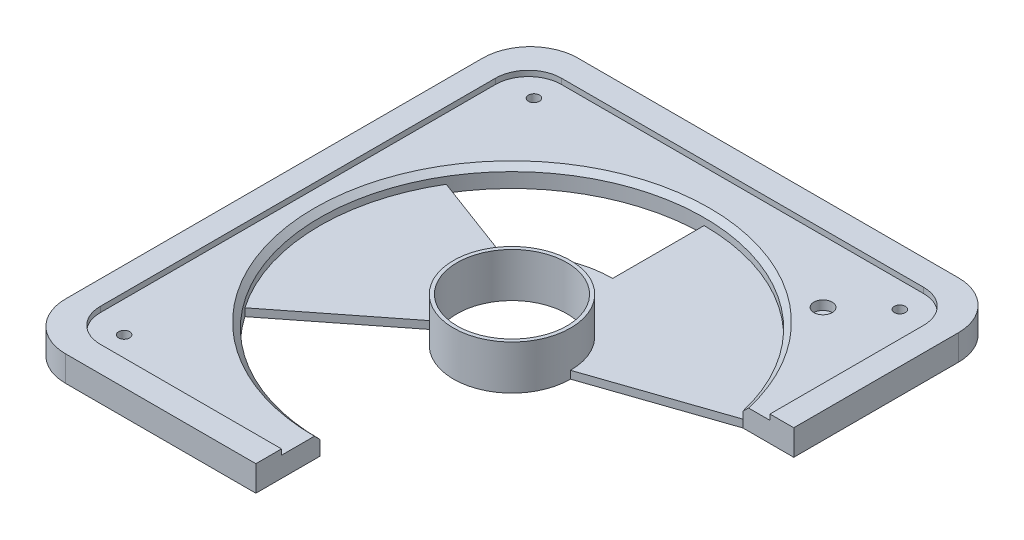
SolidWorks part; units mm, degrees
material "Alumina"
ref_plane "Front Plane" through (0, 0, 0) normal (0, 0, 1) x (1, 0, 0)
ref_plane "Top Plane" through (0, 0, 0) normal (0, 1, 0) x (1, 0, 0)
ref_plane "Right Plane" through (0, 0, 0) normal (1, 0, 0) x (0, 0, -1)
sketch "Sketch1" plane through (0, 0, 0) normal (0, 1, 0) x (1, 0, 0)
  circle A0 centre (0, 0) radius 20.32
  dimension "D1" = 40.64
extrude "Boss-Extrude1" add sketch "Sketch1" along normal blind 15.367
sketch "Sketch2" plane through (0, 15.367, 0) normal (0, 1, 0) x (1, 0, 0)
  circle A0 centre (0, 0) radius 19.05
  dimension "D1" = 38.1
extrude "Cut-Extrude1" cut sketch "Sketch2" against normal through all
sketch "Sketch3" plane through (0, 0, 0) normal (0, 1, 0) x (1, 0, 0)
  line L0 (0, 66.675) -> (0, 34.925)
  line L1 (-26.4041, 22.86) -> (-57.15, 34.3429)
  line L2 (-18.2721, -8.89) -> (-54.9803, -37.719)
  line L3 (20.32, 0) -> (64.9099, 15.24)
  circle A1 centre (0, 0) radius 66.675
  circle A2 centre (0, 0) radius 34.925
  circle A3 centre (0, 0) radius 20.32 construction
  circle A4 centre (0, 0) radius 20.32 construction
  point P8 (-66.675, 0)
  point P9 (20.32, 0)
  dimension "D1" = 133.35
  dimension "D2" = 69.85
  dimension "D3" = 57.15
  dimension "D4" = 22.86
  dimension "D5" = 37.719
  dimension "D6" = 8.89
  dimension "D7" = 15.24
extrude "Boss-Extrude2" add sketch "Sketch3" along normal blind 2.667
sketch "Sketch4" plane through (0, 2.667, 0) normal (0, 1, 0) x (1, 0, 0)
  line L0 (-29.9108, -18.0305) -> (-18.2721, -8.89)
  line L1 (-29.9108, -18.0305) -> (-54.9803, -37.719) construction
  line L2 (34.5831, 4.8749) -> (20.32, 0)
  line L3 (34.5831, 4.8749) -> (64.9099, 15.24) construction
  circle A0 centre (0, 0) radius 20.32 construction
  circle A1 centre (0, 0) radius 20.32 construction
  arc A2 (-29.9108, -18.0305) -> (34.5831, 4.8749) centre (3.5501, -9.996) ccw
  arc A3 (-18.2721, -8.89) -> (20.32, 0) centre (0, 0) ccw
  dimension "D1" = 34.412
  dimension "D2" = 20.32
extrude "Cut-Extrude2" cut sketch "Sketch4" against normal through all
sketch "Sketch6" plane through (0, 2.667, 0) normal (0, 1, 0) x (1, 0, 0)
  circle A0 centre (0, 0) radius 19.05
  dimension "D1" = 38.1
extrude "Cut-Extrude3" cut sketch "Sketch6" against normal through all
sketch "Sketch7" plane through (0, 0, 0) normal (0, 1, 0) x (1, 0, 0)
  line L1 (-82.55, -88.9) -> (82.55, -88.9)
  line L2 (-82.55, -88.9) -> (-82.55, 88.9)
  line L3 (-82.55, 88.9) -> (82.55, 88.9)
  line L4 (82.55, -88.9) -> (82.55, 88.9)
  line L5 (-82.55, -88.9) -> (82.55, 88.9) construction
  line L6 (-82.55, 88.9) -> (82.55, -88.9) construction
  circle A0 centre (0, 0) radius 66.675
  point P0 (0, 0)
  dimension "D3" = 133.35
  dimension "D1" = 165.1
  dimension "D2" = 177.8
extrude "Boss-Extrude3" add sketch "Sketch7" along normal blind 6.985 contours L2 L1 L4 L3 | A0
sketch "Sketch10" plane through (0, 6.985, 0) normal (0, 1, 0) x (1, 0, 0)
  line L1 (-82.55, -88.9) -> (82.55, -88.9)
  line L2 (-82.55, -88.9) -> (-82.55, 88.9)
  line L3 (-82.55, 88.9) -> (82.55, 88.9)
  line L4 (82.55, -88.9) -> (82.55, 88.9)
  line L5 (-82.55, -88.9) -> (82.55, 88.9) construction
  line L6 (-82.55, 88.9) -> (82.55, -88.9) construction
  line L7 (-74.295, -80.01) -> (74.295, -80.01)
  line L8 (-74.295, -80.01) -> (-74.295, 80.01)
  line L9 (-74.295, 80.01) -> (74.295, 80.01)
  line L10 (74.295, -80.01) -> (74.295, 80.01)
  line L11 (-74.295, -80.01) -> (74.295, 80.01) construction
  line L12 (-74.295, 80.01) -> (74.295, -80.01) construction
  point P0 (0, 0)
  point P7 (0, 0)
  dimension "D1" = 160.02
extrude "Boss-Extrude5" add sketch "Sketch10" along normal blind 1.905
sketch "Sketch11" plane through (0, 6.985, 0) normal (0, 1, 0) x (1, 0, 0)
  line L0 (64.9099, 15.24) -> (82.55, 15.24)
  line L1 (82.55, -88.9) -> (82.55, 88.9) construction
  line L2 (0, -66.675) -> (0, -88.9)
  line L3 (-82.55, -88.9) -> (82.55, -88.9) construction
  circle A0 centre (0, 0) radius 66.675 construction
  arc A1 (0, -66.675) -> (64.9099, 15.24) centre (164.1808, -130.0978) cw
  arc A2 (82.55, 15.24) -> (0, -88.9) centre (50.3237, -44.0027) cw
  dimension "D1" = 176.0051
  dimension "D2" = 67.4406
extrude "Cut-Extrude4" cut sketch "Sketch11" against normal through all
sketch "Sketch12" plane through (0, 8.89, 0) normal (0, 1, 0) x (1, 0, 0)
  line L0 (74.295, 15.24) -> (82.55, 15.24)
  line L1 (0, -80.01) -> (0, -88.9)
  line L2 (-82.55, -88.9) -> (82.55, -88.9) construction
  arc A0 (0, -80.01) -> (74.295, 15.24) centre (212.0939, -168.8432) cw
  arc A1 (82.55, 15.24) -> (0, -88.9) centre (48.6936, -42.7106) cw
  dimension "D1" = 229.946
  dimension "D2" = 67.1158
extrude "Cut-Extrude5" cut sketch "Sketch12" against normal through all
fillet "Fillet1" radius 16.51 3 edges at (-82.55, 4.445, 88.9) (82.55, 4.445, -88.9) (-82.55, 4.445, -88.9)
fillet "Fillet2" radius 11.43 3 edges at (-74.295, 7.9375, 80.01) (74.295, 7.9375, -80.01) (-74.295, 7.9375, -80.01)
chamfer "Chamfer1" distance 1.905 angle 45 1 edges at (-52.2575, 6.985, -41.4091)
sketch "Sketch13" plane through (0, 6.985, 0) normal (0, 1, 0) x (1, 0, 0)
  line L0 (-82.55, -72.39) -> (-82.55, 72.39) construction
  line L1 (82.55, 15.24) -> (82.55, 72.39) construction
  line L2 (-66.04, 88.9) -> (66.04, 88.9) construction
  circle A0 centre (63.5, 71.12) radius 1.905
  circle A1 centre (-63.5, 71.12) radius 1.905
  circle A2 centre (-63.5, -71.12) radius 1.905
  dimension "D1" = 3.81
  dimension "D2" = 17.78
  dimension "D3" = 19.05
  dimension "D4" = 19.05
  dimension "D5" = 17.78
extrude "Cut-Extrude6" cut sketch "Sketch13" against normal through all
sketch "Sketch14" plane through (0, 6.985, 0) normal (0, 1, 0) x (1, 0, 0)
  line L0 (-66.04, 88.9) -> (66.04, 88.9) construction
  line L1 (82.55, 15.24) -> (82.55, 72.39) construction
  circle A0 centre (49.53, 58.42) radius 3.175
  dimension "D1" = 6.35
  dimension "D2" = 30.48
  dimension "D3" = 33.02
extrude "Cut-Extrude7" cut sketch "Sketch14" against normal blind 3.175
